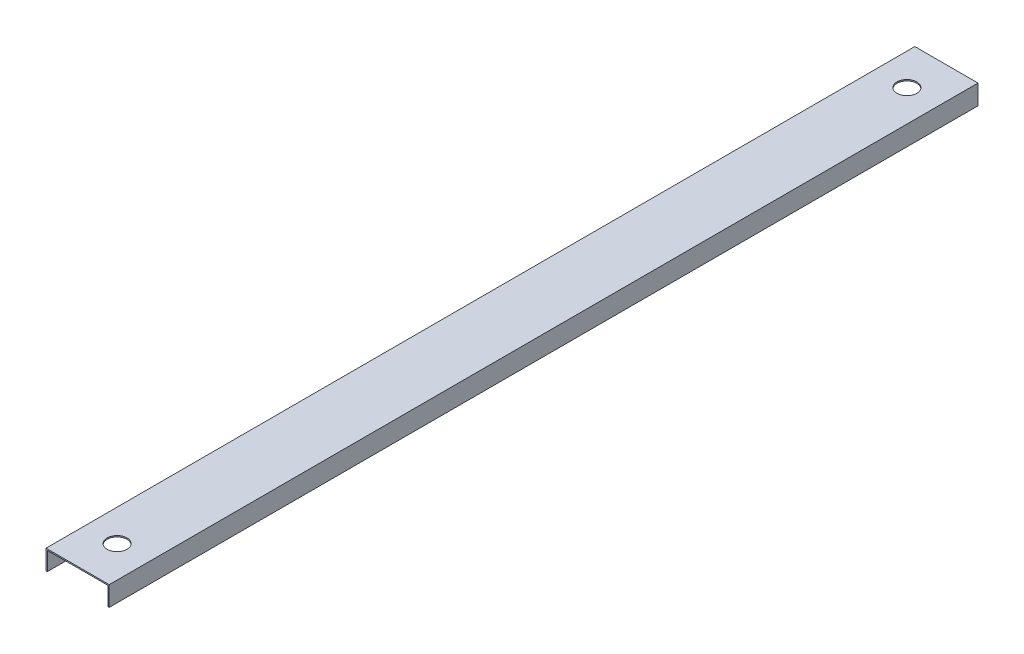
SolidWorks part; units mm, degrees
ref_plane "Front Plane" through (0, 0, 0) normal (0, 0, 1) x (1, 0, 0)
ref_plane "Top Plane" through (0, 0, 0) normal (0, 1, 0) x (1, 0, 0)
ref_plane "Right Plane" through (0, 0, 0) normal (1, 0, 0) x (0, 0, -1)
sketch "Sketch1" plane through (0, 0, 0) normal (0, 0, 1) x (1, 0, 0)
  line L0 (-10.16, 0) -> (-10.16, 6.35)
  line L1 (-10.16, 6.35) -> (10.16, 6.35)
  line L2 (10.16, 6.35) -> (10.16, 0)
  line L3 (-9.7536, 0) -> (-9.7536, 5.9436)
  line L4 (-9.7536, 5.9436) -> (9.7536, 5.9436)
  line L5 (9.7536, 5.9436) -> (9.7536, 0)
  line L6 (-10.16, 0) -> (-9.7536, 0)
  line L7 (10.16, 0) -> (9.7536, 0)
  point P2 (0, 6.35)
  dimension "D1" = 20.32
  dimension "D2" = 6.35
  dimension "D3" = 0.4064
extrude "Boss-Extrude1" add sketch "Sketch1" against normal blind 279.4
sketch "Sketch2" plane through (0, 6.35, 0) normal (0, 1, 0) x (1, 0, 0)
  line L0 (-10.16, 139.7) -> (10.16, 139.7) construction
  line L1 (-10.16, 279.4) -> (-10.16, 0) construction
  line L2 (10.16, 279.4) -> (10.16, 0) construction
  line L3 (0, 12.7) -> (0, 266.7) construction
  line L4 (10.16, 0) -> (-10.16, 0) construction
  circle A0 centre (0, 266.7) radius 3.1877
  circle A1 centre (0, 12.7) radius 3.1877
  point P10 (0, 139.7)
  dimension "D1" = 6.3754
  dimension "D2" = 12.7
extrude "Cut-Extrude1" cut sketch "Sketch2" against normal through all
sketch "Sketch3" [suppressed] plane through (0, 6.35, 0) normal (0, 1, 0) x (1, 0, 0)
  line L1 (-10.16, 279.4) -> (-6.35, 279.4)
  line L2 (-10.16, 279.4) -> (-10.16, 247.65)
  line L3 (-10.16, 247.65) -> (-6.35, 247.65)
  line L4 (-6.35, 279.4) -> (-6.35, 247.65)
  line L5 (10.16, 279.4) -> (6.35, 279.4)
  line L6 (10.16, 279.4) -> (10.16, 247.65)
  line L7 (10.16, 247.65) -> (6.35, 247.65)
  line L8 (6.35, 279.4) -> (6.35, 247.65)
  line L9 (-10.16, 0) -> (-6.35, 0)
  line L10 (-10.16, 0) -> (-10.16, 31.75)
  line L11 (-10.16, 31.75) -> (-6.35, 31.75)
  line L12 (-6.35, 0) -> (-6.35, 31.75)
  line L13 (10.16, 0) -> (6.35, 0)
  line L14 (10.16, 0) -> (10.16, 31.75)
  line L15 (10.16, 31.75) -> (6.35, 31.75)
  line L16 (6.35, 0) -> (6.35, 31.75)
  dimension "D1" = 31.75
  dimension "D2" = 12.7
extrude "Cut-Extrude2" [suppressed] cut sketch "Sketch3" against normal through all
